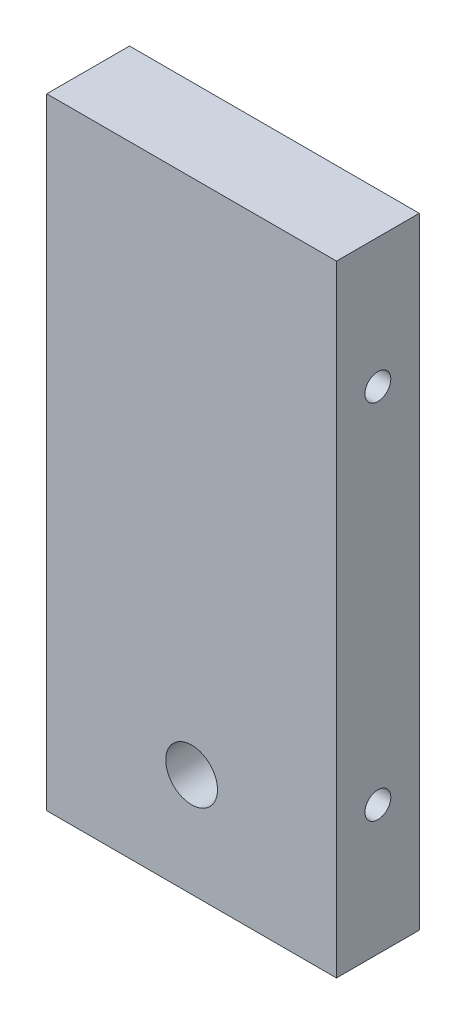
SolidWorks part; units mm, degrees
material "2024-T3"
ref_plane "正面" through (0, 0, 0) normal (0, 0, 1) x (1, 0, 0)
ref_plane "平面" through (0, 0, 0) normal (0, 1, 0) x (1, 0, 0)
ref_plane "右側面" through (0, 0, 0) normal (1, 0, 0) x (0, 0, -1)
sketch "ｽｹｯﾁ1" plane through (0, 0, 0) normal (0, 0, 1) x (1, 0, 0)
  line L1 (0, 0) -> (28, 0)
  line L2 (0, 0) -> (0, 60)
  line L3 (0, 60) -> (28, 60)
  line L4 (28, 0) -> (28, 60)
  dimension "D1" = 60
  dimension "D2" = 28
extrude "ﾎﾞｽ - 押し出し1" add sketch "ｽｹｯﾁ1" along normal blind 8
sketch "ｽｹｯﾁ2" plane through (0, 0, 8) normal (0, 0, 1) x (1, 0, 0)
  line L0 (0, 0) -> (28, 0) construction
  line L1 (28, 0) -> (28, 60) construction
  circle A0 centre (14, 10) radius 2.5
  dimension "D1" = 5
  dimension "D2" = 10
  dimension "D3" = 14
extrude "ｶｯﾄ - 押し出し1" cut sketch "ｽｹｯﾁ2" against normal through all
hole_wizard "M3x0.5 ねじ穴1" positions "3Dｽｹｯﾁ1" profile "ｽｹｯﾁ3" tap size "M3x0.5" standard "JIS"
sketch3d "3Dｽｹｯﾁ1"
  line L0 (0, 60, 8) -> (0, 60, 0) construction
  line L1 (0, 0, 8) -> (0, 0, 0) construction
  line L2 (0, 60, 0) -> (0, 0, 0) construction
  point P0 (0, 47.5, 4)
  point P2 (0, 12.5, 4)
  dimension "D1" = 12.5
  dimension "D2" = 12.5
  dimension "D3" = 4
  dimension "D4" = 4
sketch "ｽｹｯﾁ3" plane through (0, 47.5, 4) normal (0, 1, 0) x (0, 0, 1)
  line L0 (0, 0) -> (0, 8.2511)
  line L1 (0, 8.2511) -> (1.25, 7.5)
  line L2 (1.25, 7.5) -> (1.25, 0)
  line L5 (1.25, 0) -> (0, 0)
  line L10 (0, 8.2511) -> (-1.25, 7.5) construction
  line L11 (0, -6.35) -> (0, 107.95) construction
  dimension "ねじ下穴ﾄﾞﾘﾙ直径" = 2.5
  dimension "ねじ下穴ﾄﾞﾘﾙの深さ" = 7.5
  dimension "ﾄﾞﾘﾙ角度" = 118
cosmetic thread "穴のねじ山1" parameters "D1"=5, "D2"=3
cosmetic thread "穴のねじ山2" parameters "D1"=5, "D2"=3
hole_wizard "M3x0.5 ねじ穴2" positions "3Dｽｹｯﾁ2" profile "ｽｹｯﾁ4" tap size "M3x0.5" standard "JIS"
sketch3d "3Dｽｹｯﾁ2"
  line L0 (28, 60, 8) -> (28, 60, 0) construction
  line L1 (28, 0, 8) -> (28, 60, 8) construction
  line L2 (28, 0, 8) -> (28, 0, 0) construction
  point P0 (28, 47.5, 4)
  point P2 (28, 12.5, 4)
  dimension "D1" = 12.5
  dimension "D2" = 4
  dimension "D3" = 12.5
  dimension "D4" = 4
sketch "ｽｹｯﾁ4" plane through (28, 47.5, 4) normal (0, 1, 0) x (0, 0, -1)
  line L0 (0, 0) -> (0, 8.2511)
  line L1 (0, 8.2511) -> (1.25, 7.5)
  line L2 (1.25, 7.5) -> (1.25, 0)
  line L5 (1.25, 0) -> (0, 0)
  line L10 (0, 8.2511) -> (-1.25, 7.5) construction
  line L11 (0, -6.35) -> (0, 107.95) construction
  dimension "ねじ下穴ﾄﾞﾘﾙ直径" = 2.5
  dimension "ねじ下穴ﾄﾞﾘﾙの深さ" = 7.5
  dimension "ﾄﾞﾘﾙ角度" = 118
cosmetic thread "穴のねじ山3" parameters "D1"=5, "D2"=3
cosmetic thread "穴のねじ山4" parameters "D1"=5, "D2"=3
